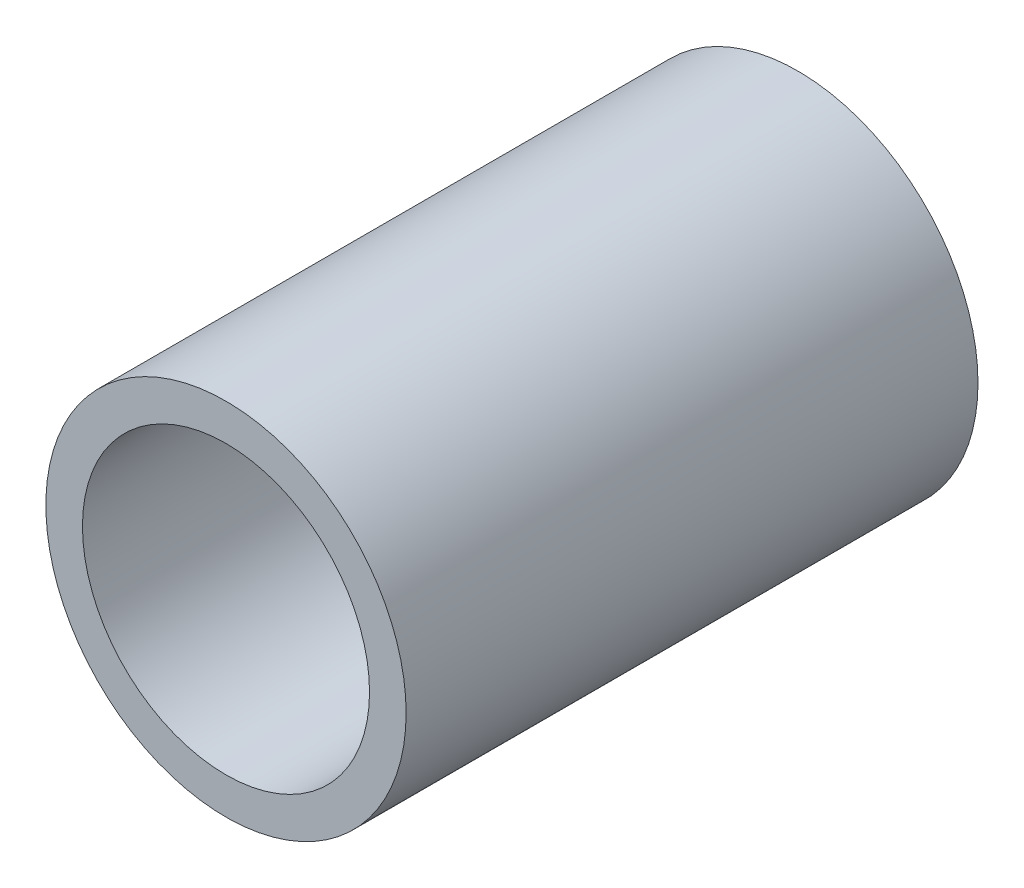
SolidWorks part; units mm, degrees
ref_plane "Front Plane" through (0, 0, 0) normal (0, 0, 1) x (1, 0, 0)
ref_plane "Top Plane" through (0, 0, 0) normal (0, 1, 0) x (1, 0, 0)
ref_plane "Right Plane" through (0, 0, 0) normal (1, 0, 0) x (0, 0, -1)
sketch "Sketch1" plane through (0, 0, 0) normal (0, 0, 1) x (1, 0, 0)
  circle A0 centre (0, 0) radius 4.0005
  circle A1 centre (0, 0) radius 3.1877
  dimension "D1" = 8.001
  dimension "ID" = 6.3754
extrude "Extrude1" add sketch "Sketch1" along normal mid plane 12.7
sketch "Sketch2" plane through (0, 0, 0) normal (1, 0, 0) x (0, 0, -1)
  line L0 (-6.35, -3.1877) -> (6.35, -3.1877) construction
  line L3 (6.35, 3.1877) -> (-6.35, 3.1877) construction
  line L5 (-6.35, -3.1877) -> (6.35, -3.1877)
  line L6 (6.35, 3.1877) -> (-6.35, 3.1877)
sketch "Sketch4" plane through (0, 0, 6.35) normal (0, 0, 1) x (1, 0, 0)
  line L0 (0, 0) -> (-2.254, 2.254)
  line L1 (0, -3.4925) -> (0, 3.4925) construction
  circle A0 centre (0, 0) radius 3.1877 construction
  dimension "D1" = 45
